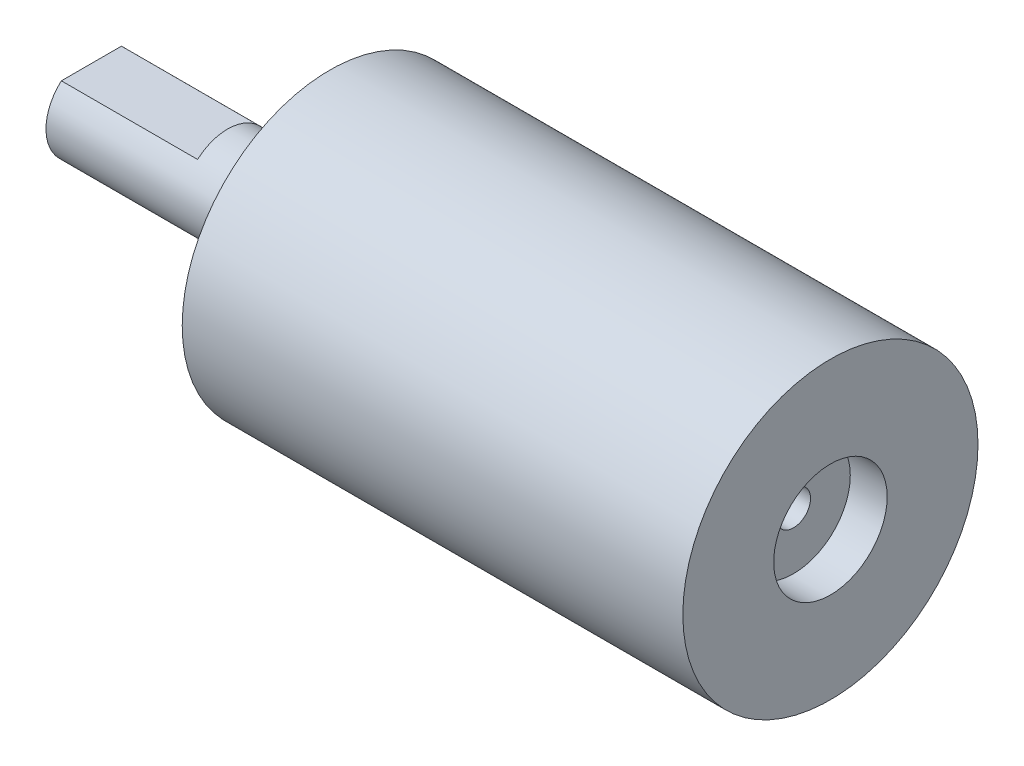
SolidWorks part; units mm, degrees
material "1023 Carbon Steel Sheet (SS)"
ref_plane "Płaszczyzna przednia" through (0, 0, 0) normal (0, 0, 1) x (1, 0, 0)
ref_plane "Płaszczyzna górna" through (0, 0, 0) normal (0, 1, 0) x (1, 0, 0)
ref_plane "Płaszczyzna prawa" through (0, 0, 0) normal (1, 0, 0) x (0, 0, -1)
sketch "Szkic1" plane through (0, 0, 0) normal (0, 0, 1) x (1, 0, 0)
  line L0 (0, 0) -> (-14908.854, 0) construction
  line L1 (0, 0) -> (0, 4)
  line L2 (0, 4) -> (19, 4)
  line L3 (19, 4) -> (19, 9.5)
  line L4 (19, 9.5) -> (21, 9.5)
  line L5 (21, 9.5) -> (21, 13)
  line L6 (21, 13) -> (65.1, 13)
  line L7 (65.1, 13) -> (65.1, 5)
  line L8 (65.1, 5) -> (61.85, 5)
  line L9 (61.85, 5) -> (61.85, 1.5)
  line L10 (61.85, 1.5) -> (54.1, 1.5)
  line L11 (54.1, 1.5) -> (54.1, 0)
  line L12 (0, 0) -> (54.1, 0)
  dimension "D1" = 26
  dimension "D2" = 19
  dimension "D3" = 8
  dimension "D4" = 3
  dimension "D5" = 10
  dimension "D6" = 44.1
  dimension "D7" = 11
  dimension "D8" = 3.25
  dimension "D9" = 19
  dimension "D10" = 2
revolve "Obrót1" add sketch "Szkic1" angle 360 about L0
sketch "Szkic2" plane through (21, 0, 0) normal (-1, 0, 0) x (0, 0, 1)
  circle A0 centre (0, 0) radius 11.25 construction
  circle A1 centre (0, 11.25) radius 1
  circle A2 centre (9.7428, 5.625) radius 1
  circle A3 centre (9.7428, -5.625) radius 1
  circle A4 centre (0, -11.25) radius 1
  circle A5 centre (-9.7428, -5.625) radius 1
  circle A6 centre (-9.7428, 5.625) radius 1
  point P18 (0, 0)
  dimension "D1" = 22.5
  dimension "D2" = 2
  dimension "D3" = 6
extrude "Wytnij-wyciągnięcie1" cut sketch "Szkic2" against normal blind 3.6
sketch "Szkic3" plane through (0, 0, 0) normal (-1, 0, 0) x (0, 0, 1)
  line L0 (-2.6458, 3) -> (2.6458, 3)
  circle A0 centre (0, 0) radius 4 construction
  arc A1 (2.6458, 3) -> (-2.6458, 3) centre (0, 0) ccw
  point P5 (0, 4)
  dimension "D1" = 1
extrude "Wytnij-wyciągnięcie2" cut sketch "Szkic3" against normal blind 12
